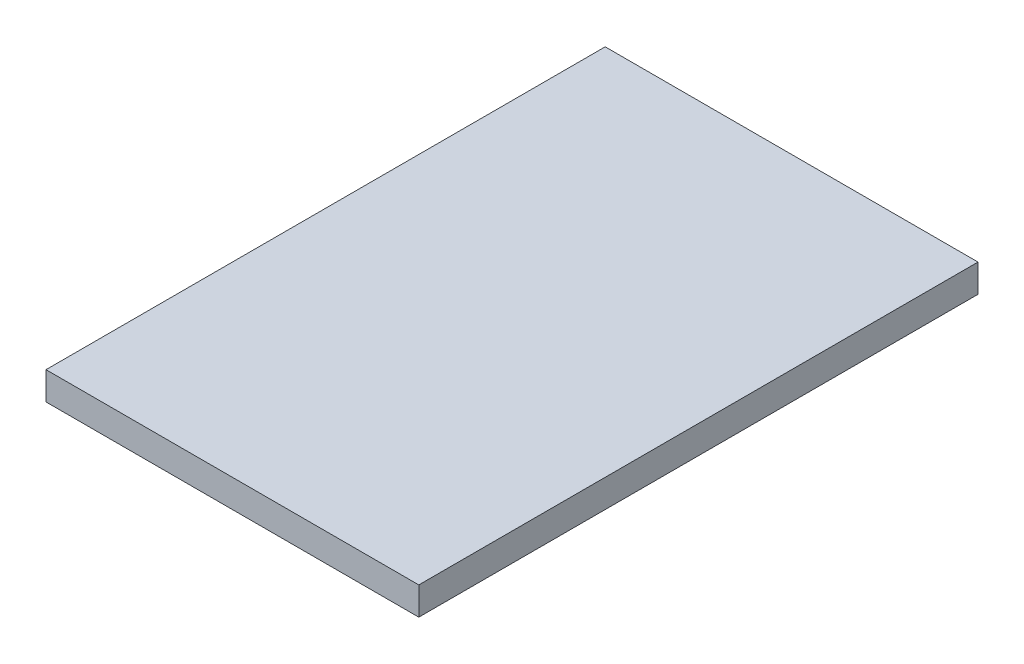
SolidWorks part; units mm, degrees
material "Pine"
ref_plane "Front Plane" through (0, 0, 0) normal (0, 0, 1) x (1, 0, 0)
ref_plane "Top Plane" through (0, 0, 0) normal (0, 1, 0) x (1, 0, 0)
ref_plane "Right Plane" through (0, 0, 0) normal (1, 0, 0) x (0, 0, -1)
sketch "Sketch1" plane through (0, 0, 0) normal (0, 1, 0) x (1, 0, 0)
  line L1 (0, 0) -> (254, 0)
  line L2 (0, 0) -> (0, 381)
  line L3 (0, 381) -> (254, 381)
  line L4 (254, 0) -> (254, 381)
  dimension "D1" = 254
  dimension "D2" = 381
extrude "Boss-Extrude1" add sketch "Sketch1" along normal blind 19.05
ref_plane "Center_Plane" through (127, 0, 0) normal (1, 0, 0) x (0, 0, -1)
